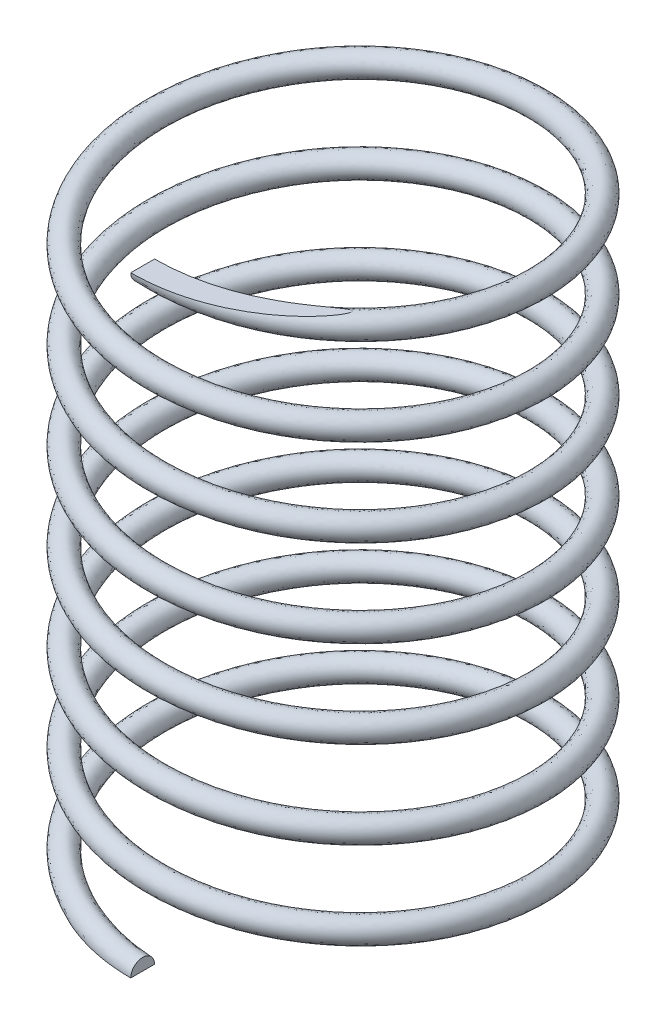
SolidWorks part; units mm, degrees
material "AISI 321 Stal nierdzewna odprężona (SS)"
ref_plane "Płaszczyzna przednia" through (0, 0, 0) normal (0, 0, 1) x (1, 0, 0)
ref_plane "Płaszczyzna górna" through (0, 0, 0) normal (0, 1, 0) x (1, 0, 0)
ref_plane "Płaszczyzna prawa" through (0, 0, 0) normal (1, 0, 0) x (0, 0, -1)
sketch "Szkic2" plane through (0, 0, 0) normal (0, 1, 0) x (1, 0, 0)
  circle A0 centre (0, 0) radius 6
  point P4 (0, 0)
  dimension "D1" = 12
curve "Helisa/Spirala1" pitch 2.75 height 19.25 turns 7
ref_plane "Płaszczyzna2" through (0, 0, 0) normal (1, 0, 0) x (0, 0, -1)
sketch "Szkic5" plane through (0, 0, 0) normal (1, 0, 0) x (0, 0, -1)
  circle A0 centre (-6, 0) radius 0.375
  spline S0 degree 3 poles (-6, 0) (-6, 0.0569) (-5.6876, 0.172) (-4.3531, 0.3437) (-2.3559, 0.5156) (0, 0.6875) (2.3559, 0.8594) (4.3531, 1.0312) (5.6876, 1.2031) (6.1562, 1.375) (5.6876, 1.5469) (4.3531, 1.7187) (2.3559, 1.8906) (0, 2.0625) (-2.3559, 2.2344) (-4.3531, 2.4062) (-5.6876, 2.5781) (-6.1562, 2.75) (-5.6876, 2.9219) (-4.3531, 3.0937) (-2.3559, 3.2656) (0, 3.4375) (2.3559, 3.6094) (4.3531, 3.7813) (5.6876, 3.9531) (6.1562, 4.125) (5.6876, 4.2969) (4.3531, 4.4688) (2.3559, 4.6406) (0, 4.8125) (-2.3559, 4.9844) (-4.3531, 5.1563) (-5.6876, 5.3281) (-6.1562, 5.5) (-5.6876, 5.6719) (-4.3531, 5.8438) (-2.3559, 6.0156) (0, 6.1875) (2.3559, 6.3594) (4.3531, 6.5313) (5.6876, 6.7031) (6.1562, 6.875) (5.6876, 7.0469) (4.3531, 7.2188) (2.3559, 7.3906) (0, 7.5625) (-2.3559, 7.7344) (-4.3531, 7.9063) (-5.6876, 8.0781) (-6.1562, 8.25) (-5.6876, 8.4219) (-4.3531, 8.5938) (-2.3559, 8.7656) (0, 8.9375) (2.3559, 9.1094) (4.3531, 9.2813) (5.6876, 9.4531) (6.1562, 9.625) (5.6876, 9.7969) (4.3531, 9.9688) (2.3559, 10.1406) (0, 10.3125) (-2.3559, 10.4844) (-4.3531, 10.6563) (-5.6876, 10.8281) (-6.1562, 11) (-5.6876, 11.1719) (-4.3531, 11.3438) (-2.3559, 11.5156) (0, 11.6875) (2.3559, 11.8594) (4.3531, 12.0313) (5.6876, 12.2031) (6.1562, 12.375) (5.6876, 12.5469) (4.3531, 12.7188) (2.3559, 12.8906) (0, 13.0625) (-2.3559, 13.2344) (-4.3531, 13.4063) (-5.6876, 13.5781) (-6.1562, 13.75) (-5.6876, 13.9219) (-4.3531, 14.0938) (-2.3559, 14.2656) (0, 14.4375) (2.3559, 14.6094) (4.3531, 14.7813) (5.6876, 14.9531) (6.1562, 15.125) (5.6876, 15.2969) (4.3531, 15.4688) (2.3559, 15.6406) (0, 15.8125) (-2.3559, 15.9844) (-4.3531, 16.1563) (-5.6876, 16.3281) (-6.1562, 16.5) (-5.6876, 16.6719) (-4.3531, 16.8438) (-2.3559, 17.0156) (0, 17.1875) (2.3559, 17.3594) (4.3531, 17.5313) (5.6876, 17.7031) (6.1562, 17.875) (5.6876, 18.0469) (4.3531, 18.2188) (2.3559, 18.3906) (0, 18.5625) (-2.3559, 18.7344) (-4.3531, 18.9063) (-5.6876, 19.078) (-6, 19.1931) (-6, 19.25) knots 0 0 0 0 0.008929 0.017857 0.026786 0.035714 0.044643 0.053571 0.0625 0.071429 0.080357 0.089286 0.098214 0.107143 0.116071 0.125 0.133929 0.142857 0.151786 0.160714 0.169643 0.178571 0.1875 0.196429 0.205357 0.214286 0.223214 0.232143 0.241071 0.25 0.258929 0.267857 0.276786 0.285714 0.294643 0.303571 0.3125 0.321429 0.330357 0.339286 0.348214 0.357143 0.366071 0.375 0.383929 0.392857 0.401786 0.410714 0.419643 0.428571 0.4375 0.446429 0.455357 0.464286 0.473214 0.482143 0.491071 0.5 0.508929 0.517857 0.526786 0.535714 0.544643 0.553571 0.5625 0.571429 0.580357 0.589286 0.598214 0.607143 0.616071 0.625 0.633929 0.642857 0.651786 0.660714 0.669643 0.678571 0.6875 0.696429 0.705357 0.714286 0.723214 0.732143 0.741071 0.75 0.758929 0.767857 0.776786 0.785714 0.794643 0.803571 0.8125 0.821429 0.830357 0.839286 0.848214 0.857143 0.866071 0.875 0.883929 0.892857 0.901786 0.910714 0.919643 0.928571 0.9375 0.946429 0.955357 0.964286 0.973214 0.982143 0.991071 1 1 1 1 construction
  point P3 (-6, 0)
  dimension "D1" = 0.75
sweep "Wyciągnięcie po ścieżce2" add profiles "Szkic5" path "Helisa/Spirala1"
sketch "Szkic12" plane through (0, 0, 0) normal (1, 0, 0) x (0, 0, -1)
  line L0 (-6.375, 0) -> (25.0276, 0)
  line L1 (25.0276, 0) -> (25.0276, -3.1028)
  line L2 (25.0276, -3.1028) -> (-6.375, -3.1028)
  line L3 (-6.375, -3.1028) -> (-6.375, 0)
  line L4 (-19.3061, 19.25) -> (-19.3061, 22.3528)
  line L5 (-19.3061, 22.3528) -> (14.3442, 22.3528)
  line L6 (14.3442, 19.25) -> (-19.3061, 19.25)
  line L7 (14.3442, 22.3528) -> (14.3442, 19.25)
  circle A0 centre (-6, 0) radius 0.375 construction
extrude "Wytnij-wyciągnięcie1" cut sketch "Szkic12" against normal through all both and the other way through all
